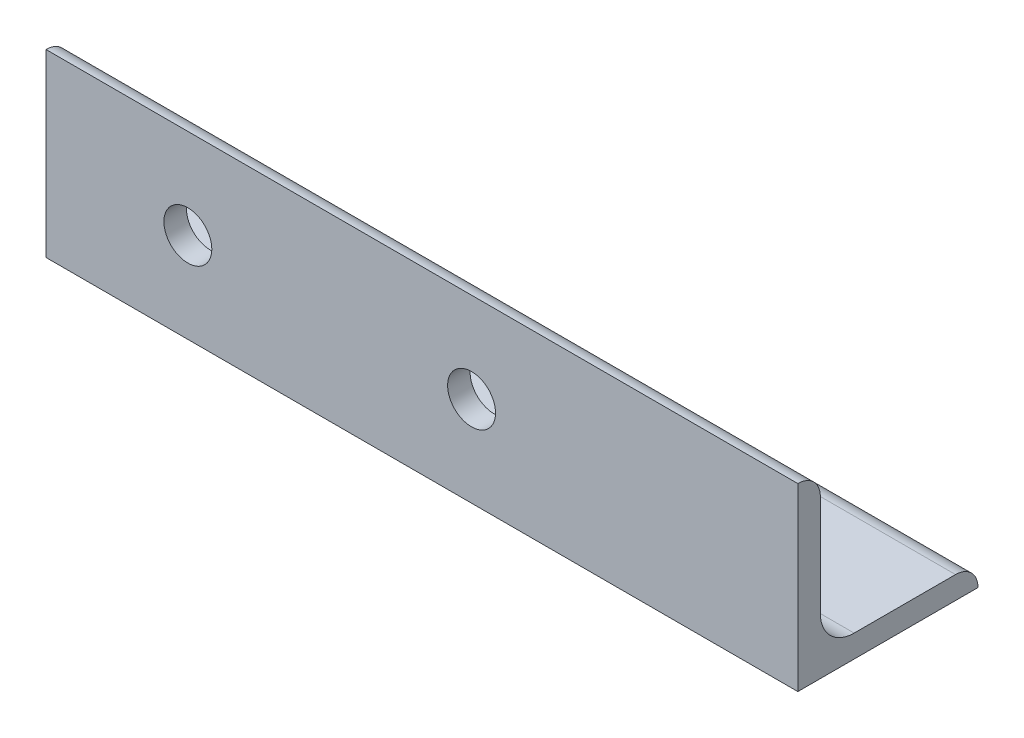
SolidWorks part; units mm, degrees
ref_plane "Alzado" through (0, 0, 0) normal (0, 0, 1) x (1, 0, 0)
ref_plane "Planta" through (0, 0, 0) normal (0, 1, 0) x (1, 0, 0)
ref_plane "Vista lateral" through (0, 0, 0) normal (1, 0, 0) x (0, 0, -1)
sketch "Croquis1" plane through (0, 0, 0) normal (0, 1, 0) x (1, 0, 0)
  line L0 (-95.2248, 0) -> (10.7752, 0)
  dimension "D1" = 106
other "Miembro estructural1"
ref_plane "Plano1" through (-95.2248, 0, 0) normal (1, 0, 0) x (0, 0, -1)
sketch "Sketch12" plane through (-95.2248, 0, 0) normal (1, 0, 0) x (0, 0, -1)
  line L0 (0, 0) -> (0, 25.4)
  line L1 (0, 25.4) -> (0.0051, 25.4)
  line L2 (3.175, 22.2301) -> (3.175, 7.9375)
  line L3 (7.9375, 3.175) -> (22.2301, 3.175)
  line L4 (25.4, 0.0051) -> (25.4, 0)
  line L5 (25.4, 0) -> (0, 0)
  arc A0 (25.4, 0.0051) -> (22.2301, 3.175) centre (22.2301, 0.0051) ccw
  arc A1 (0.0051, 25.4) -> (3.175, 22.2301) centre (0.0051, 22.2301) cw
  arc A2 (7.9375, 3.175) -> (3.175, 7.9375) centre (7.9375, 7.9375) cw
  point P10 (12.7, 0)
  point P14 (0, 12.7)
  point P15 (3.175, 12.7)
  point P16 (12.7, 3.175)
  point P17 (3.175, 25.4)
  point P18 (25.4, 3.175)
  point P19 (0, 0)
  dimension "D2" = 0.0051
  dimension "Radius_1" = 4.7625
  dimension "D1" = 3.175
  dimension "H_leg" = 25.4
hole_wizard "Taladro de margen para 1/41" positions "Croquis3" profile "Croquis2" hole size "1/4" standard "Ansi Inch" end condition up to next
sketch "Croquis3" plane through (0, 0, 0) normal (0, 0, 1) x (1, 0, 0)
  line L0 (10.7752, 12.7) -> (-95.2248, 12.7) construction
  line L1 (10.7752, 25.4) -> (10.7752, 0) construction
  line L2 (-95.2248, 25.4) -> (-95.2248, 0) construction
  point P0 (-35.2248, 12.7)
  point P2 (-75.2248, 12.7)
  dimension "D1" = 40
  dimension "D2" = 20
sketch "Croquis2" plane through (-35.2248, 12.7, 0) normal (1, 0, 0) x (0, -1, 0)
  line L0 (0, 0) -> (0, 3.175)
  line L1 (0, 3.175) -> (3.3782, 3.175)
  line L2 (3.3782, 3.175) -> (3.3782, 0)
  line L5 (3.3782, 0) -> (0, 0)
  line L11 (0, -6.35) -> (0, 107.95) construction
  dimension "Diámetro de taladro hasta el siguiente" = 6.7564
  dimension "Profundidad de taladro hasta el siguiente" = 3.175
